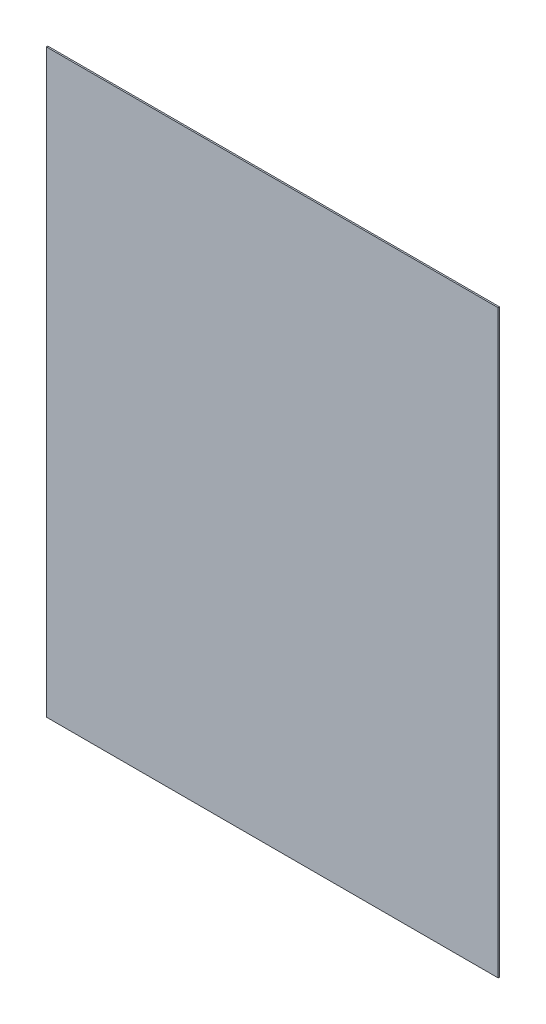
SolidWorks part; units mm, degrees
material "6061 Alloy"
ref_plane "Front Plane" through (0, 0, 0) normal (0, 0, 1) x (1, 0, 0)
ref_plane "Top Plane" through (0, 0, 0) normal (0, 1, 0) x (1, 0, 0)
ref_plane "Right Plane" through (0, 0, 0) normal (1, 0, 0) x (0, 0, -1)
ref_plane "Plane1" through (0, 0, -53.4312) normal (0, 0, 1) x (1, 0, 0)
sketch "Sketch1" plane through (0, 0, -53.4312) normal (0, 0, 1) x (1, 0, 0)
  line L0 (-145, 140) -> (-145, -176)
  line L1 (-145, -176) -> (101, -176)
  line L2 (101, -176) -> (101, 140)
  line L3 (101, 140) -> (-145, 140)
extrude "Boss-Extrude1" add sketch "Sketch1" against normal blind 0.7937
ref_plane "Plane2" through (-22, 0, 0) normal (-1, 0, 0) x (0, 0, 1)
ref_plane "Plane3" through (0, -18, 0) normal (0, -1, 0) x (-1, 0, 0)
